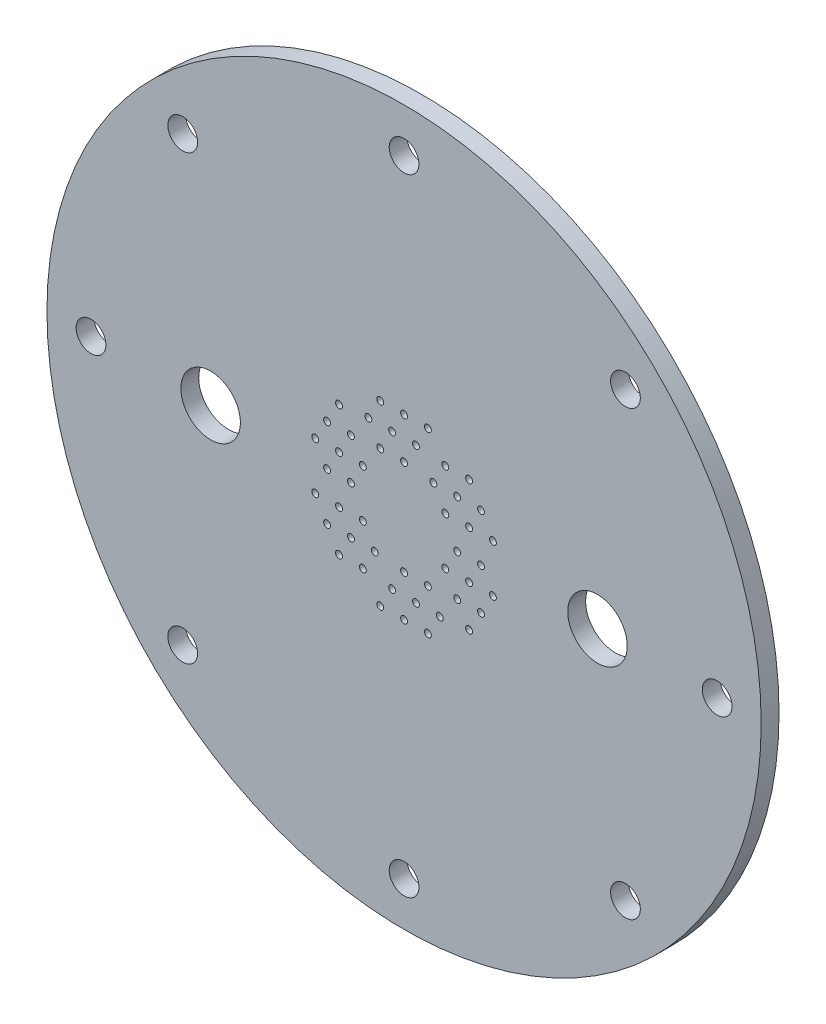
SolidWorks part; units mm, degrees
ref_plane "Front Plane" through (0, 0, 0) normal (0, 0, 1) x (1, 0, 0)
ref_plane "Top Plane" through (0, 0, 0) normal (0, 1, 0) x (1, 0, 0)
ref_plane "Right Plane" through (0, 0, 0) normal (1, 0, 0) x (0, 0, -1)
sketch "Sketch1" plane through (0, 0, 0) normal (0, 0, 1) x (1, 0, 0)
  circle A0 centre (0, 0) radius 76.2
  dimension "D1" = 152.4
extrude "Boss-Extrude1" add sketch "Sketch1" along normal blind 3.81
sketch "Sketch2" plane through (0, 0, 0) normal (0, 0, -1) x (-1, 0, 0)
  line L0 (0, 0) -> (0, 10.16) construction
  line L1 (0, 10.16) -> (5.08, 10.16) construction
  line L2 (5.08, 10.16) -> (7.62, 14.5594) construction
  line L3 (7.62, 14.5594) -> (2.54, 14.5594) construction
  line L4 (2.54, 14.5594) -> (5.08, 10.16) construction
  line L5 (0, 10.16) -> (2.54, 14.5594) construction
  line L6 (0, 10.16) -> (-2.54, 14.5594) construction
  line L7 (-2.54, 14.5594) -> (2.54, 14.5594) construction
  line L8 (2.54, 14.5594) -> (5.08, 18.9588) construction
  line L9 (5.08, 18.9588) -> (7.62, 14.5594) construction
  line L10 (-2.54, 14.5594) -> (-5.08, 18.9588) construction
  line L11 (-5.08, 18.9588) -> (0, 18.9588) construction
  line L12 (0, 18.9588) -> (-2.54, 14.5594) construction
  line L13 (0, 18.9588) -> (2.54, 14.5594) construction
  line L14 (0, 18.9588) -> (5.08, 18.9588) construction
  circle A0 centre (0, 10.16) radius 0.7366
  circle A1 centre (2.54, 14.5594) radius 0.7366
  circle A2 centre (5.08, 10.16) radius 0.7366
  circle A3 centre (7.62, 14.5594) radius 0.7366
  circle A4 centre (-2.54, 14.5594) radius 0.7366
  circle A5 centre (-5.08, 18.9588) radius 0.7366
  circle A6 centre (0, 18.9588) radius 0.7366
  circle A7 centre (5.08, 18.9588) radius 0.7366
  dimension "D3" = 1.4732
  dimension "D1" = 5.08
  dimension "D2" = 10.16
extrude "Cut-Extrude1" cut sketch "Sketch2" against normal through all
pattern_circular "CirPattern1" count 6 over 360 about axis through (0, 0, 0) along (0, 0, 1) of "Cut-Extrude1"
sketch "Sketch3" plane through (0, 0, 0) normal (0, 0, -1) x (-1, 0, 0)
  line L0 (-41.275, 0) -> (41.275, 0) construction
  circle A0 centre (41.275, 0) radius 6.35
  circle A1 centre (-41.275, 0) radius 6.35
  point P4 (0, 0)
  dimension "D2" = 12.7
  dimension "D1" = 82.55
extrude "Cut-Extrude2" cut sketch "Sketch3" against normal through all
sketch "Sketch5" plane through (0, 0, 0) normal (0, 0, -1) x (-1, 0, 0)
  line L0 (0, 0) -> (66.802, 0) construction
  circle A0 centre (66.802, 0) radius 3.175
  dimension "D2" = 6.35
  dimension "D1" = 66.802
extrude "Cut-Extrude3" cut sketch "Sketch5" against normal through all
pattern_circular "CirPattern2" count 8 over 360 about axis through (0, 0, 0) along (0, 0, 1) of "Cut-Extrude3"
sketch "Sketch6" plane through (0, 0, 0) normal (1, 0, 0) x (0, 0, -1)
  line L0 (0, -76.2) -> (0, 76.2) construction
  line L1 (0, 53.34) -> (1.27, 53.34)
  line L2 (0, 53.34) -> (0, 50.8)
  line L3 (0, 50.8) -> (1.27, 50.8)
  line L4 (1.27, 53.34) -> (1.27, 50.8)
  line L5 (0, 76.2) -> (-3.81, 76.2) construction
  line L6 (0, 0) -> (-3.81, 0) construction
  line L7 (-3.81, 76.2) -> (-3.81, -76.2) construction
  dimension "D1" = 2.54
  dimension "D2" = 25.4
  dimension "D3" = 1.27
revolve "Revolve1" add sketch "Sketch6" angle 360 about L6
equation "\"Top Injector Diameter\"=6"
equation "\"D1@Sketch1\"=\"Top Injector Diameter\""
equation "\"Top Injector Height\"=0.15"
equation "\"D1@Boss-Extrude1\"=\"Top Injector Height\""
equation "\"Distance Between Holes\"=0.2"
equation "\"D1@Sketch2\"=\"Distance Between Holes\""
equation "\"Top Injector Hole Distance from Center\"=0.4"
equation "\"D2@Sketch2\"=\"Top Injector Hole Distance from Center\""
equation "\"Top Injector Hole Diameter\"=0.058"
equation "\"D3@Sketch2\"=\"Top Injector Hole Diameter\""
equation "\"Top Injector Manifold Valves\"=3.25"
equation "\"D1@Sketch3\"=\"Top Injector Manifold Valves\""
equation "\"Top Injector Valves Diameter\"=0.5"
equation "\"D2@Sketch3\"=\"Top Injector Valves Diameter\""
equation "\"Top Injector Screw Holes Distance\"=2.63"
equation "\"D1@Sketch5\"=\"Top Injector Screw Holes Distance\""
equation "\"Top Injector Screw Hole Diameter\"=0.25"
equation "\"D2@Sketch5\"=\"Top Injector Screw Hole Diameter\""
